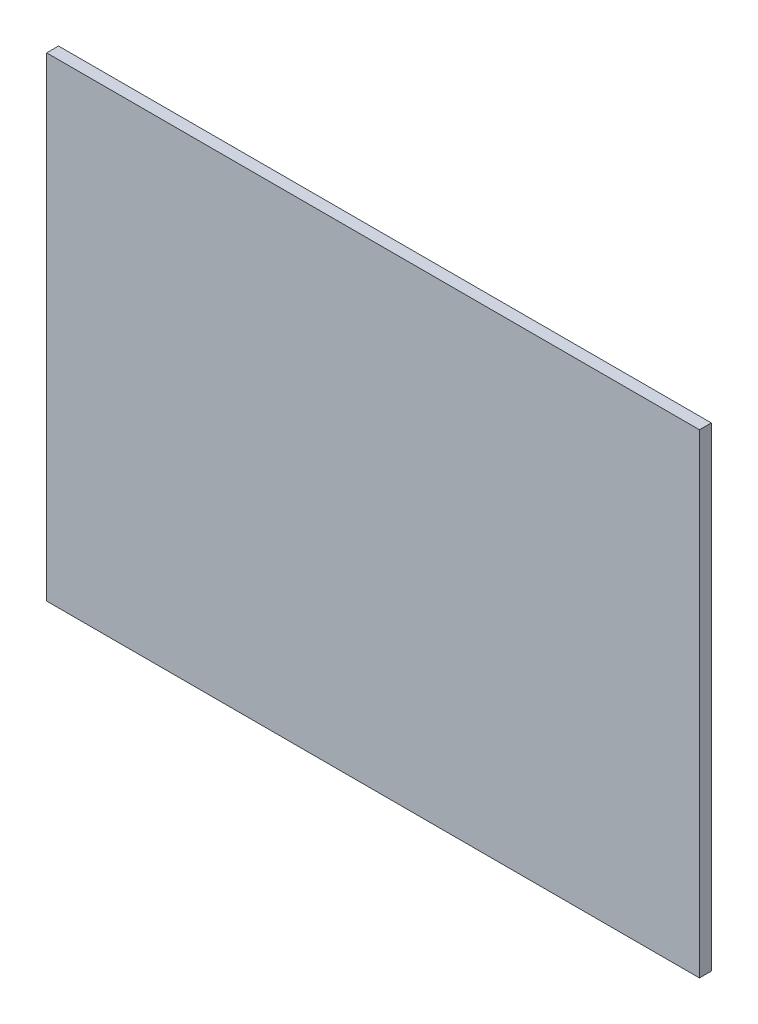
SolidWorks part; units mm, degrees
ref_plane "Front Plane" through (0, 0, 0) normal (0, 0, 1) x (1, 0, 0)
ref_plane "Top Plane" through (0, 0, 0) normal (0, 1, 0) x (1, 0, 0)
ref_plane "Right Plane" through (0, 0, 0) normal (1, 0, 0) x (0, 0, -1)
sketch "Sketch1" plane through (0, 0, 0) normal (0, 0, 1) x (1, 0, 0)
  line L1 (-110, 80) -> (110, 80)
  line L2 (-110, 80) -> (-110, -80)
  line L3 (-110, -80) -> (110, -80)
  line L4 (110, 80) -> (110, -80)
  line L5 (-110, 80) -> (110, -80) construction
  line L6 (-110, -80) -> (110, 80) construction
  point P0 (0, 0)
  dimension "D1" = 220
  dimension "D2" = 160
extrude "Boss-Extrude1" add sketch "Sketch1" along normal blind 4
